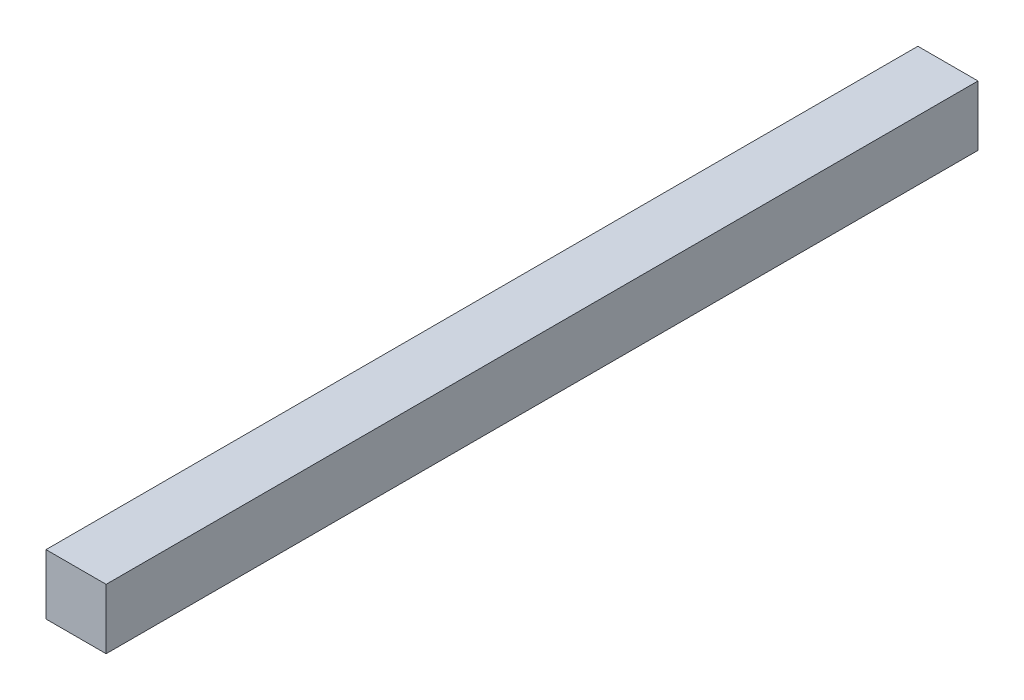
SolidWorks part; units mm, degrees
material "Pine"
ref_plane "Front Plane" through (0, 0, 0) normal (0, 0, 1) x (1, 0, 0)
ref_plane "Top Plane" through (0, 0, 0) normal (0, 1, 0) x (1, 0, 0)
ref_plane "Right Plane" through (0, 0, 0) normal (1, 0, 0) x (0, 0, -1)
sketch "Sketch1" plane through (0, 0, 0) normal (0, 0, 1) x (1, 0, 0)
  line L1 (0, 0) -> (38.1, 0)
  line L2 (0, 0) -> (0, 38.1)
  line L3 (0, 38.1) -> (38.1, 38.1)
  line L4 (38.1, 0) -> (38.1, 38.1)
  dimension "D1" = 38.1
  dimension "D2" = 38.1
extrude "Boss-Extrude1" add sketch "Sketch1" along normal blind 552.45
